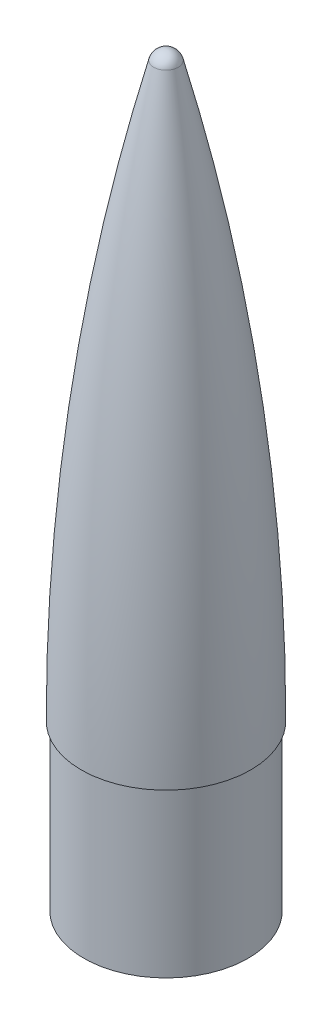
SolidWorks part; units mm, degrees
material "ABS"
ref_plane "Front Plane" through (0, 0, 0) normal (0, 0, 1) x (1, 0, 0)
ref_plane "Top Plane" through (0, 0, 0) normal (0, 1, 0) x (1, 0, 0)
ref_plane "Right Plane" through (0, 0, 0) normal (1, 0, 0) x (0, 0, -1)
sketch "Sketch1" plane through (0, 0, 0) normal (0, 0, 1) x (1, 0, 0)
  line L0 (0, 0) -> (32.5, 0)
  line L1 (0, 0) -> (0, 295)
  line L2 (33.5, 65) -> (32.5, 65)
  line L3 (32.5, 65) -> (32.5, 0)
  line L4 (33.5, 65) -> (33.5, 0) construction
  line L5 (33.5, 0) -> (32.5, 0) construction
  line L6 (0, 295) -> (-5, 295) construction
  arc A0 (0, 295) -> (4.8421, 291.2467) centre (0, 290) cw
  arc A1 (4.8421, 291.2467) -> (33.5, 65) centre (-873.9079, 65) cw
  dimension "D6" = 5
  dimension "D1" = 295
  dimension "D2" = 1
  dimension "D3" = 65
  dimension "D4" = 32.5
  dimension "D5" = 5
revolve "Revolve1" add sketch "Sketch1" angle 360 about L1
